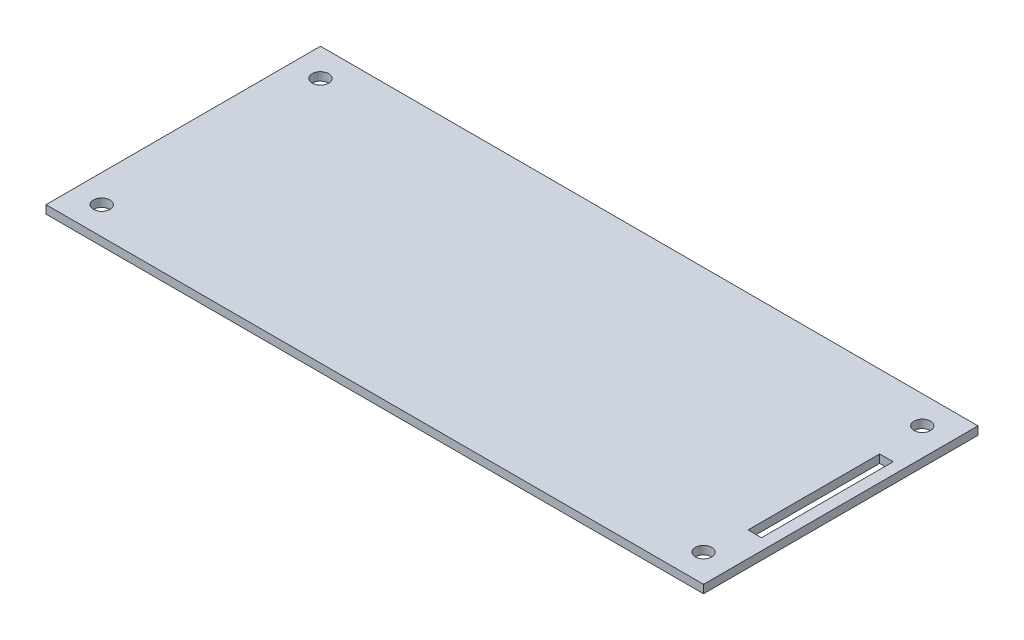
SolidWorks part; units mm, degrees
ref_plane "Front" through (0, 0, 0) normal (0, 0, 1) x (1, 0, 0)
ref_plane "Top" through (0, 0, 0) normal (0, 1, 0) x (1, 0, 0)
ref_plane "Right" through (0, 0, 0) normal (1, 0, 0) x (0, 0, -1)
sketch "Sketch1" plane through (0, 0, 0) normal (0, 1, 0) x (1, 0, 0)
  line L1 (0, 0) -> (119.888, 0)
  line L2 (0, 0) -> (0, -50.038)
  line L3 (0, -50.038) -> (119.888, -50.038)
  line L4 (119.888, 0) -> (119.888, -50.038)
  line L5 (115.356, -13.4) -> (117.816, -13.4)
  line L6 (115.356, -13.4) -> (115.356, -37.4)
  line L7 (115.356, -37.4) -> (117.816, -37.4)
  line L8 (117.816, -13.4) -> (117.816, -37.4)
  circle A0 centre (5.08, -5.08) radius 1.5
  circle A2 centre (114.808, -5.08) radius 1.5
  circle A3 centre (114.808, -44.958) radius 1.5
  circle A4 centre (5.08, -44.958) radius 1.5
  point P15 (117.816, -25.4)
  point P16 (116.586, -37.4)
  dimension "D3" = 3
  dimension "D6" = 3
  dimension "D7" = 5.08
  dimension "D8" = 5.08
  dimension "D9" = 5.08
  dimension "D10" = 5.08
  dimension "D11" = 3
  dimension "D12" = 3
  dimension "D13" = 5.08
  dimension "D14" = 5.08
  dimension "D1" = 119.888
  dimension "D2" = 50.038
  dimension "D4" = 5.08
  dimension "D5" = 5.08
  dimension "D15" = 2.46
  dimension "D16" = 24
  dimension "D17" = 24.638
  dimension "D18" = 3.302
extrude "Boss-Extrude1" add sketch "Sketch1" along normal blind 1.5
